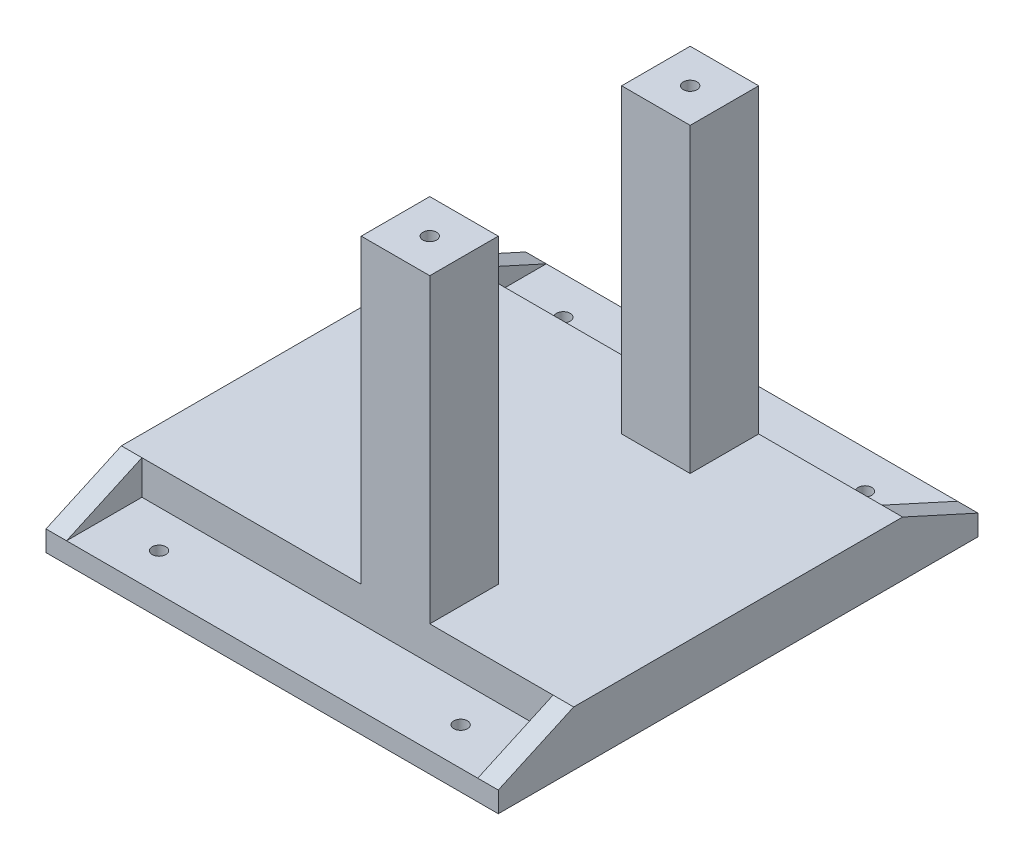
SolidWorks part; units mm, degrees
ref_plane "Front Plane" through (0, 0, 0) normal (0, 0, 1) x (1, 0, 0)
ref_plane "Top Plane" through (0, 0, 0) normal (0, 1, 0) x (1, 0, 0)
ref_plane "Right Plane" through (0, 0, 0) normal (1, 0, 0) x (0, 0, -1)
sketch "Sketch1" plane through (0, 0, 0) normal (0, 1, 0) x (1, 0, 0)
  line L0 (0, 113.3376) -> (0, -70.7921) construction
  line L1 (0, -70.7921) -> (0, 0) construction
  line L2 (0, 0) -> (-100.3898, 0) construction
  line L3 (-100.3898, 0) -> (129.7257, 0) construction
  line L5 (-33, 24) -> (33, 24)
  line L6 (-33, 24) -> (-33, -24)
  line L7 (-33, -24) -> (33, -24)
  line L8 (33, 24) -> (33, -24)
  dimension "D1" = 66
  dimension "D2" = 48
  dimension "D3" = 24
  dimension "D4" = 33
extrude "Boss-Extrude1" add sketch "Sketch1" along normal blind 5
sketch "Sketch2" plane through (0, 5, 0) normal (0, 1, 0) x (1, 0, 0)
  line L0 (33, 24) -> (-33, 24) construction
  line L1 (2, 24) -> (12, 24)
  line L2 (2, 24) -> (2, 14)
  line L3 (2, 14) -> (12, 14)
  line L4 (12, 24) -> (12, 14)
  line L5 (-33, 24) -> (-33, -24) construction
  line L6 (-33, -24) -> (33, -24) construction
  line L7 (2, -14) -> (12, -14)
  line L8 (2, -14) -> (2, -24)
  line L9 (2, -24) -> (12, -24)
  line L10 (12, -14) -> (12, -24)
  dimension "D1" = 35
  dimension "D2" = 10
  dimension "D3" = 10
  dimension "D4" = 10
  dimension "D5" = 10
  dimension "D6" = 35
extrude "Boss-Extrude2" add sketch "Sketch2" along normal blind 44
sketch "Sketch3" plane through (0, 49, 0) normal (0, 1, 0) x (1, 0, 0)
  line L0 (2, 14) -> (12, 14) construction
  line L1 (2, 24) -> (2, 14) construction
  line L2 (12, -24) -> (12, -14) construction
  line L3 (2, -24) -> (12, -24) construction
  circle A0 centre (7, 19) radius 1
  circle A1 centre (7, -19) radius 1
  dimension "D1" = 5
  dimension "D3" = 5
  dimension "D2" = 5
  dimension "D4" = 5
extrude "Cut-Extrude1" cut sketch "Sketch3" against normal blind 7
sketch "Sketch4" plane through (0, 0, 0) normal (0, -1, 0) x (1, 0, 0)
  line L1 (-33, 35) -> (33, 35)
  line L2 (-33, 35) -> (-33, -35)
  line L3 (-33, -35) -> (33, -35)
  line L4 (33, 35) -> (33, -35)
  line L5 (-33, -24) -> (-33, 24) construction
  line L7 (-33, 24) -> (33, 24) construction
  dimension "D1" = 66
  dimension "D2" = 0
  dimension "D3" = 70
  dimension "D4" = 11
extrude "Boss-Extrude3" add sketch "Sketch4" along normal blind 3
sketch "Sketch5" plane through (33, 0, 0) normal (1, 0, 0) x (0, 0, -1)
  line L0 (-24, 5) -> (-35, 0)
  line L1 (-35, 0) -> (-24, 0)
  line L2 (-24, 0) -> (-24, 5)
  line L3 (24, 5) -> (24, 0)
  line L4 (24, 0) -> (35, 0)
  line L5 (35, 0) -> (24, 5)
extrude "Boss-Extrude4" add sketch "Sketch5" against normal blind 3
mirror "Mirror1" about plane through (0, 0, 0) normal (1, 0, 0) of "Boss-Extrude4"
sketch "Sketch6" plane through (0, 0, 0) normal (0, 1, 0) x (1, 0, 0)
  line L0 (-30, 35) -> (-30, 24) construction
  line L1 (30, 24) -> (30, 35) construction
  line L2 (-30, 35) -> (30, 35) construction
  circle A0 centre (-22, 29.5) radius 1
  circle A2 centre (22, 29.5) radius 1
  dimension "D1" = 8
  dimension "D2" = 8
  dimension "D3" = 5.5
  dimension "D4" = 5.5
extrude "Cut-Extrude2" cut sketch "Sketch6" against normal blind 3
mirror "Mirror2" about plane through (0, 0, 0) normal (0, 0, 1) of "Cut-Extrude2"
